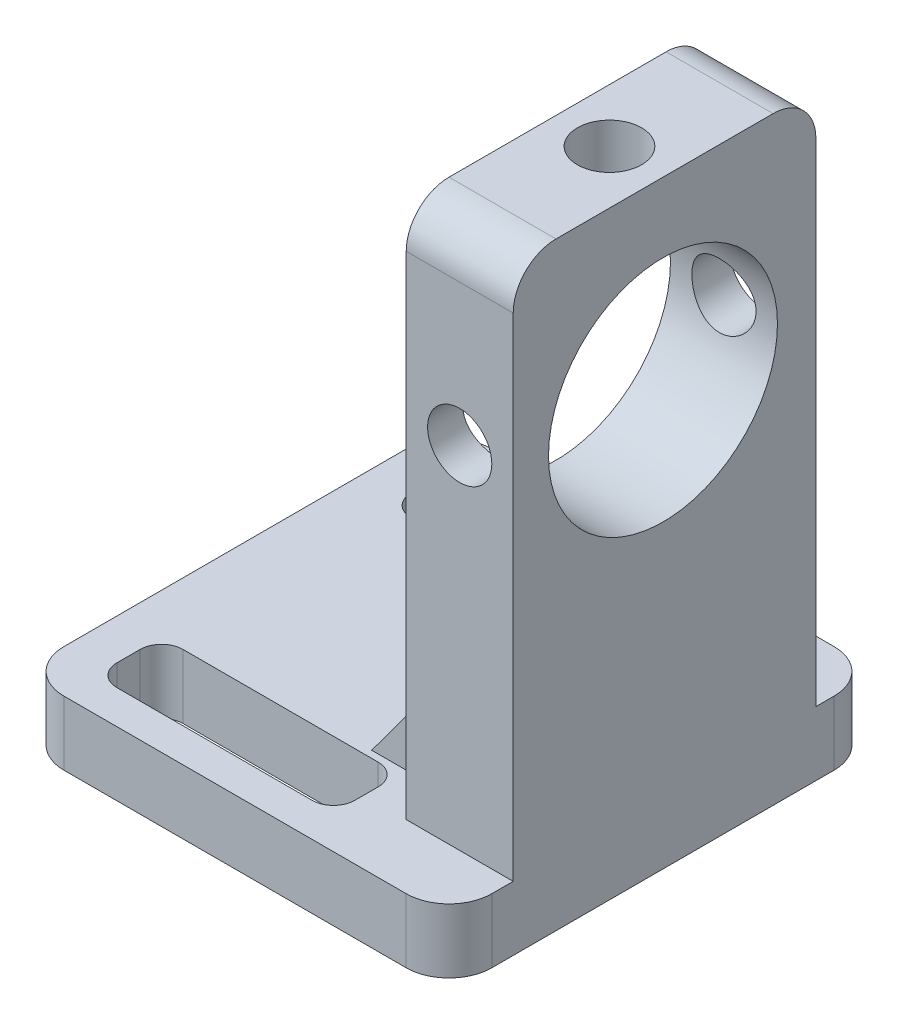
SolidWorks part; units mm, degrees
ref_plane "前视基准面" through (0, 0, 0) normal (0, 0, 1) x (1, 0, 0)
ref_plane "上视基准面" through (0, 0, 0) normal (0, 1, 0) x (1, 0, 0)
ref_plane "右视基准面" through (0, 0, 0) normal (1, 0, 0) x (0, 0, -1)
sketch "草图1" plane through (0, 0, 0) normal (0, 1, 0) x (1, 0, 0)
  line L1 (0.7445, -10) -> (-19.2555, -10)
  line L2 (0.7445, -10) -> (0.7445, 10)
  line L3 (0.7445, 10) -> (-19.2555, 10)
  line L4 (-19.2555, -10) -> (-19.2555, 10)
  point P0 (0, 0)
extrude "凸台-拉伸1" add sketch "草图1" along normal blind 3
sketch "草图2" plane through (0, 3, 0) normal (0, 1, 0) x (1, 0, 0)
  line L0 (0.7445, -10) -> (0.7445, 10) construction
  line L1 (0.7445, -7) -> (-4.2555, -7)
  line L2 (0.7445, -7) -> (0.7445, 7.1465)
  line L3 (0.7445, 7.1465) -> (-4.2555, 7.1465)
  line L4 (-4.2555, -7) -> (-4.2555, 7.1465)
  line L5 (0.7445, -7) -> (-4.2555, 7.1465) construction
  line L6 (0.7445, 7.1465) -> (-4.2555, -7) construction
  point P0 (0, 0)
extrude "凸台-拉伸2" add sketch "草图2" along normal blind 25
ref_point "点1"
sketch "草图3" plane through (0.7445, 0, 0) normal (1, 0, 0) x (0, 0, -1)
  circle A0 centre (0, 19.3914) radius 5.35
extrude "切除-拉伸2" cut sketch "草图3" against normal blind 5
ref_plane "基准面3" through (-1.7555, 0, 0) normal (-1, 0, 0) x (0, 0, 1)
sketch "草图7" plane through (0, 0, 0) normal (0, -1, 0) x (1, 0, 0)
  line L1 (-6.2345, -8.4198) -> (-17.3598, -8.4198)
  line L2 (-6.2345, -8.4198) -> (-6.2345, -5.3285)
  line L3 (-6.2345, -5.3285) -> (-17.3598, -5.3285)
  line L4 (-17.3598, -8.4198) -> (-17.3598, -5.3285)
extrude "切除-拉伸6" cut sketch "草图7" against normal blind 10
fillet "圆角3" radius 1 4 edges at (-17.3598, 1.5, -8.4198) (-17.3598, 1.5, -5.3285) (-6.2345, 1.5, -8.4198) (-6.2345, 1.5, -5.3285)
mirror "镜向2" about plane through (0, 0, 0) normal (0, 0, 1) of "圆角3", "切除-拉伸6"
sketch "草图9" plane through (0, 0, 0) normal (0, 0, 1) x (1, 0, 0)
  line L0 (-3.2624, 2.2925) -> (-8.391, 2.2925)
  line L1 (-8.391, 2.2925) -> (-3.2624, 9.2377)
  line L2 (-3.2624, 9.2377) -> (-3.2624, 2.2925)
extrude "凸台-拉伸3" add sketch "草图9" along normal blind 5 and the other way blind 5 separate body
fillet "圆角1" radius 2 4 edges at (0.7445, 1.5, 10) (-19.2555, 1.5, 10) (-19.2555, 1.5, -10) (0.7445, 1.5, -10)
fillet "圆角2" radius 2 2 edges at (-1.7555, 28, 7) (-1.7555, 28, -7.1465)
ref_point "点2"
ref_plane "基准面4" through (0, 19.3914, 0) normal (0, 1, 0) x (1, 0, 0)
sketch "草图11" plane through (0, 0, -7.1465) normal (0, 0, -1) x (-1, 0, 0)
  line L0 (1.7555, 26) -> (1.7555, 3) construction
  line L1 (4.2555, 26) -> (-0.7445, 26) construction
  line L2 (-0.7445, 3) -> (4.2555, 3) construction
  line L5 (2.75, 19.3914) -> (-2.75, 19.3914) construction
  line L6 (1.7555, -12.65) -> (1.7555, 12.65) construction
  circle A0 centre (1.7555, 19.3914) radius 1.5
extrude "切除-拉伸7" cut sketch "草图11" against normal blind 5
mirror "镜向3" about plane through (0, 0, 0) normal (0, 0, 1) of "切除-拉伸7"
sketch "草图12" plane through (0, 28, 0) normal (0, 1, 0) x (1, 0, 0)
  circle A0 centre (-1.7555, 0) radius 1.5
extrude "切除-拉伸8" cut sketch "草图12" against normal blind 5
